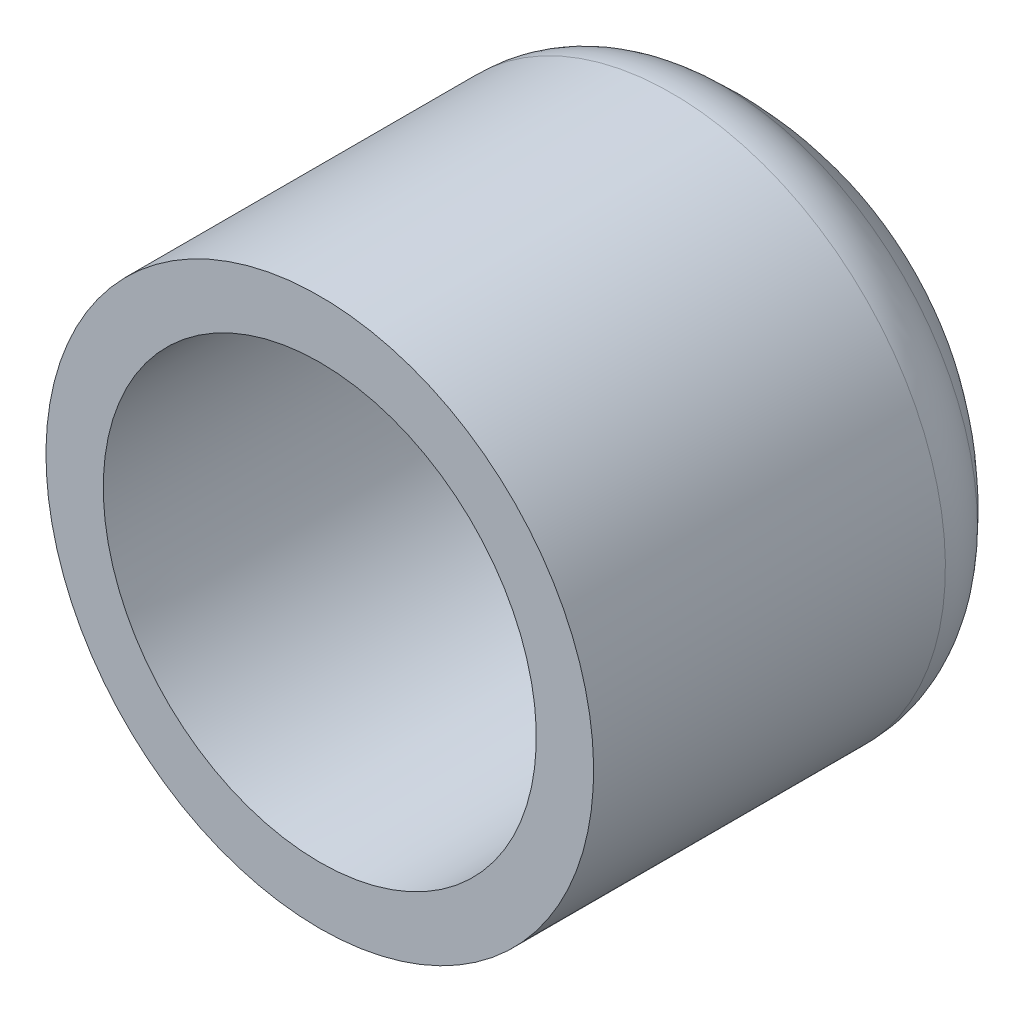
SolidWorks part; units mm, degrees
ref_plane "Front Plane" through (0, 0, 0) normal (0, 0, 1) x (1, 0, 0)
ref_plane "Top Plane" through (0, 0, 0) normal (0, 1, 0) x (1, 0, 0)
ref_plane "Right Plane" through (0, 0, 0) normal (1, 0, 0) x (0, 0, -1)
sketch "Sketch1" plane through (0, 0, 0) normal (1, 0, 0) x (0, 0, -1)
  line L0 (-16.0401, 0) -> (16.0401, 0) construction
  line L1 (-16.0401, -13.4366) -> (-16.0401, 13.4366) construction
  line L2 (-16.0401, -13.4366) -> (-16.0401, -16.9926) construction
  line L3 (4.2799, -12.5222) -> (4.2799, 12.5222) construction
  line L4 (4.2799, -13.2842) -> (4.2799, 13.2842) construction
  line L5 (-16.0401, -16.9926) -> (5.7531, -16.9926) construction
  line L6 (-16.0401, 13.4366) -> (-16.0401, 16.9926) construction
  line L7 (-16.0401, 16.9926) -> (5.7531, 16.9926) construction
  line L8 (4.2799, 12.5222) -> (4.9487, 12.5222) construction
  line L9 (4.2799, -12.5222) -> (4.9487, -12.5222) construction
  line L10 (5.7531, -16.9926) -> (7.5055, -16.9926) construction
  line L11 (5.7531, 16.9926) -> (7.5055, 16.9926) construction
  line L12 (-16.0401, -13.4366) -> (4.2799, -13.2842) construction
  line L13 (-16.0401, 13.4366) -> (4.2799, 13.2842) construction
  arc A0 (7.9706, -11.1228) -> (7.9706, 11.1228) centre (-5.1435, 0) ccw construction
  arc A1 (4.9487, -12.5222) -> (7.9706, -11.1228) centre (4.9487, -8.5598) ccw construction
  arc A2 (7.9706, 11.1228) -> (4.9487, 12.5222) centre (4.9487, 8.5598) ccw construction
  arc A4 (7.5055, -16.9926) -> (7.5055, 16.9926) centre (-5.1435, 0) ccw construction
  point P0 (12.0523, 0)
  point P4 (0, 0)
  point P9 (-16.0401, 0)
  point P13 (4.2799, 0)
  point P15 (4.2799, 0)
  dimension "Int. Dome Rad" = 17.1958
  dimension "Int. Dome Fillet" = 3.9624
  dimension "Dome Thickness" = 3.9878
  dimension "Socket to Dome" = 7.7724
  dimension "Socket Depth" = 20.32
  dimension "Int. Shoulder Dia" = 25.0444
  dimension "Socket Bottom Dia" = 26.5684
  dimension "Socket Top Dia" = 26.8732
  dimension "Wall Thickness" = 3.556
  dimension "Ext. Body Length" = 21.7932
sketch "Sketch2" plane through (0, 0, 0) normal (1, 0, 0) x (0, 0, -1)
  line L0 (-16.0401, -13.4366) -> (-16.0401, -16.9926)
  line L1 (-16.0401, -16.9926) -> (7.5055, -16.9926)
  line L2 (-16.0401, -13.4366) -> (4.2799, -13.2842)
  line L3 (4.2799, -13.2842) -> (4.2799, -12.5222)
  line L4 (4.2799, -12.5222) -> (4.9487, -12.5222)
  line L5 (12.0523, 0) -> (16.0401, 0)
  arc A0 (7.5055, -16.9926) -> (7.5055, 16.9926) centre (-5.1435, 0) ccw construction
  arc A1 (7.9706, -11.1228) -> (7.9706, 11.1228) centre (-5.1435, 0) ccw construction
  arc A2 (4.9487, -12.5222) -> (7.9706, -11.1228) centre (4.9487, -8.5598) ccw construction
  arc A3 (7.5055, -16.9926) -> (16.0401, 0) centre (-5.1435, 0) ccw
  arc A4 (7.9706, -11.1228) -> (12.0523, 0) centre (-5.1435, 0) ccw
  arc A5 (4.9487, -12.5222) -> (7.9706, -11.1228) centre (4.9487, -8.5598) ccw
revolve "Revolve1" add sketch "Sketch2" angle 360 about L0
fillet "Fillet1" radius 4.826 1 edges at (0, -16.9926, -7.5055)
sketch "Sketch3" plane through (0, 0, 16.0401) normal (0, 0, 1) x (1, 0, 0)
  circle A0 centre (0, 0) radius 13.4366 construction
  circle A1 centre (0, 0) radius 13.4366
  point P3 (0, -13.4366)
  point P4 (13.4366, 0)
  point P5 (-13.4366, 0)
  point P6 (0, 13.4366)
